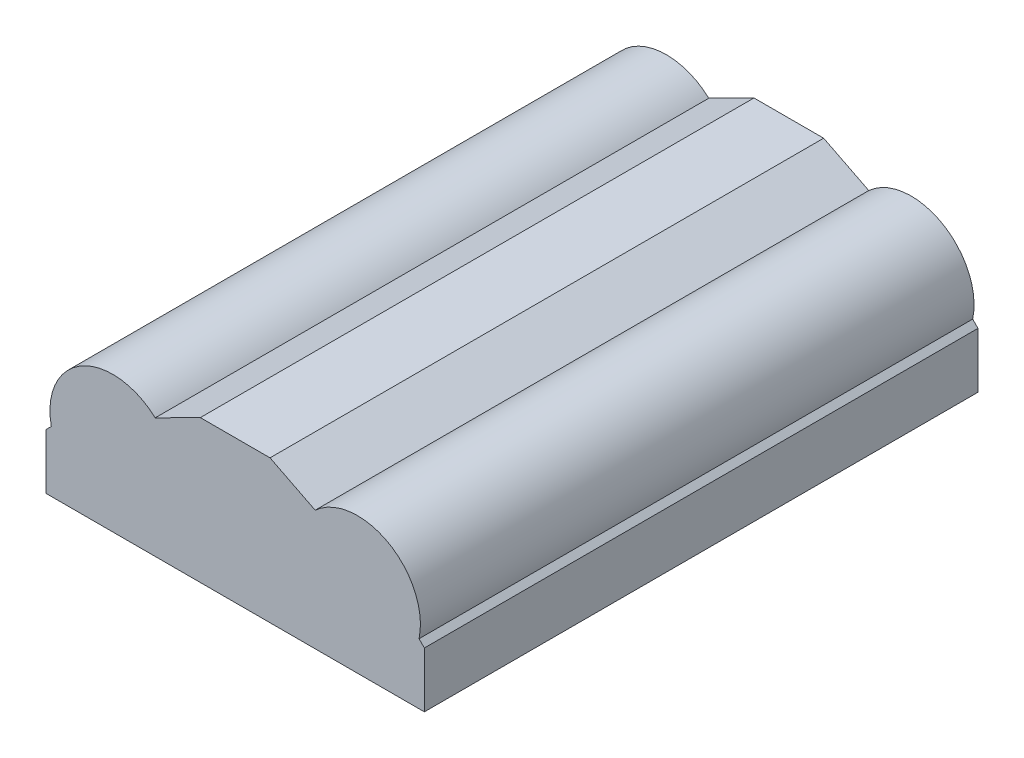
SolidWorks part; units mm, degrees
ref_plane "Front Plane" through (0, 0, 0) normal (0, 0, 1) x (1, 0, 0)
ref_plane "Top Plane" through (0, 0, 0) normal (0, 1, 0) x (1, 0, 0)
ref_plane "Right Plane" through (0, 0, 0) normal (1, 0, 0) x (0, 0, -1)
sketch "Sketch1" plane through (0, 0, 0) normal (0, 1, 0) x (1, 0, 0)
  line L1 (0, 0) -> (190, 0)
  line L2 (0, 0) -> (0, 278)
  line L3 (0, 278) -> (190, 278)
  line L4 (190, 0) -> (190, 278)
  dimension "D1" = 190
  dimension "D2" = 278
extrude "Boss-Extrude1" add sketch "Sketch1" along normal blind 105
sketch "Sketch3" plane through (0, 0, 0) normal (0, 0, 1) x (1, 0, 0)
  line L0 (-9.88, 24.131) -> (184.12, 24.131) construction
  line L1 (95, 0) -> (95, 105) construction
  line L2 (0, 0) -> (190, 0) construction
  line L3 (0, 105) -> (190, 105) construction
  line L4 (54.8363, 60.2883) -> (77.4995, 71.7241)
  line L5 (77.4995, 71.7241) -> (112.5005, 71.7241)
  line L6 (2.6748, 30.4663) -> (0, 27.7915)
  line L7 (0, 105) -> (0, 0) construction
  line L8 (0, 27.7915) -> (0, 0)
  line L9 (0, 0) -> (190, 0)
  line L10 (190, 27.7915) -> (190, 0)
  line L11 (187.3252, 30.4663) -> (190, 27.7915)
  line L12 (135.1637, 60.2883) -> (112.5005, 71.7241)
  arc A0 (54.8363, 60.2883) -> (2.6748, 30.4663) centre (33.5397, 37.0094) ccw
  arc A1 (135.1637, 60.2883) -> (187.3252, 30.4663) centre (156.4603, 37.0094) cw
  point P23 (95, 71.7241)
extrude "Cut-Extrude1" cut sketch "Sketch3" against normal through all flip side to cut
sketch "Sketch4" plane through (0, 0, 0) normal (0, -1, 0) x (1, 0, 0)
  line L0 (95, 0) -> (95, -278) construction
  line L1 (0, 0) -> (190, 0) construction
  line L2 (190, -278) -> (0, -278) construction
  line L3 (65, -251.5) -> (65, -26.5) construction
  line L4 (65, -26.5) -> (125, -26.5) construction
  line L5 (125, -26.5) -> (125, -251.5) construction
  line L6 (125, -251.5) -> (65, -251.5) construction
  line L7 (65, -70.5) -> (125, -70.5) construction
  line L8 (125, -207.5) -> (65, -207.5) construction
  line L9 (65, -139) -> (125, -139) construction
  circle A0 centre (65, -26.5) radius 4
  circle A1 centre (65, -70.5) radius 4
  circle A2 centre (125, -70.5) radius 4
  circle A3 centre (125, -26.5) radius 4
  circle A4 centre (65, -207.5) radius 4
  circle A5 centre (65, -251.5) radius 4
  circle A6 centre (125, -251.5) radius 4
  circle A7 centre (125, -207.5) radius 4
  point P26 (95, -139)
  point P27 (95, -139)
  dimension "D1" = 8
  dimension "D2" = 60
  dimension "D3" = 225
  dimension "D4" = 44
  dimension "D5" = 44
equation "\"width\"= 190"
equation "\"D1@Sketch1\"=\"width\""
equation "\"length\"= 278"
equation "\"D2@Sketch1\"=\"length\""
equation "\"height\"= 105"
equation "\"D1@Boss-Extrude1\"=\"height\""
equation "\"D5@Sketch4\"=\"D4@Sketch4\""
